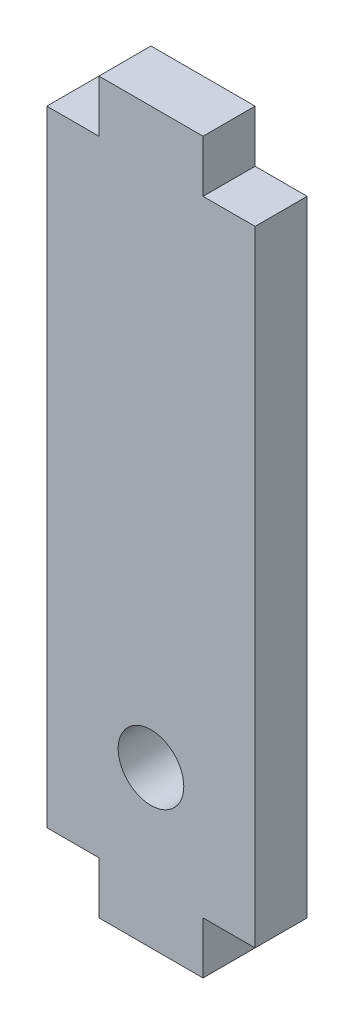
SolidWorks part; units mm, degrees
material "1060 Alloy"
ref_plane "Front Plane" through (0, 0, 0) normal (0, 0, 1) x (1, 0, 0)
ref_plane "Top Plane" through (0, 0, 0) normal (0, 1, 0) x (1, 0, 0)
ref_plane "Right Plane" through (0, 0, 0) normal (1, 0, 0) x (0, 0, -1)
sketch "Sketch1" plane through (0, 0, 0) normal (0, 0, 1) x (1, 0, 0)
  line L0 (55, 0) -> (-55, 0) construction
  line L1 (-12.7, -38.1) -> (12.7, -38.1)
  line L2 (-12.7, -38.1) -> (-12.7, 38.1)
  line L3 (-12.7, 38.1) -> (12.7, 38.1)
  line L4 (12.7, -38.1) -> (12.7, 38.1)
  line L5 (-12.7, -38.1) -> (12.7, 38.1) construction
  line L6 (-12.7, 38.1) -> (12.7, -38.1) construction
  line L7 (-12.7, 38.1) -> (12.7, 38.1)
  line L8 (-12.7, 38.1) -> (-12.7, 44.45)
  line L9 (-12.7, 44.45) -> (12.7, 44.45)
  line L10 (12.7, 38.1) -> (12.7, 44.45)
  line L11 (-12.7, -44.45) -> (12.7, -44.45)
  line L12 (12.7, -38.1) -> (12.7, -44.45)
  line L13 (-12.7, -38.1) -> (12.7, -38.1)
  line L14 (-12.7, -38.1) -> (-12.7, -44.45)
  line L15 (0, 44.45) -> (0, -44.45) construction
  line L16 (-6.35, -38.1) -> (6.35, -38.1)
  line L17 (-6.35, -38.1) -> (-6.35, -44.45)
  line L18 (-6.35, -44.45) -> (6.35, -44.45)
  line L19 (6.35, -38.1) -> (6.35, -44.45)
  line L21 (-6.35, 38.1) -> (6.35, 38.1)
  line L22 (-6.35, 38.1) -> (-6.35, 44.45)
  line L23 (-6.35, 44.45) -> (6.35, 44.45)
  line L24 (6.35, 38.1) -> (6.35, 44.45)
  point P0 (0, 0)
  point P10 (0, 44.45)
  point P11 (0, 38.1)
  point P18 (0, -38.1)
  point P19 (0, -44.45)
  point P30 (-6.35, 41.275)
  dimension "D1" = 25.4
  dimension "D2" = 76.2
  dimension "D3" = 25.4
  dimension "D4" = 6.35
  dimension "D5" = 12.7
  dimension "D6" = 12.7
extrude "Boss-Extrude1" add sketch "Sketch1" along normal blind 6.35 contours L1 L4 L3 L2 | L17 L16 L19 L18 | L22 L21 L24 L23
sketch "Sketch2" plane through (0, 0, 6.35) normal (0, 0, 1) x (1, 0, 0)
  line L8 (-12.7, -38.1) -> (-6.35, -38.1) construction
  circle A1 centre (0, -25.4) radius 4
  dimension "D2" = 12.7
  dimension "D1" = 8
extrude "Cut-Extrude1" cut sketch "Sketch2" against normal through all
